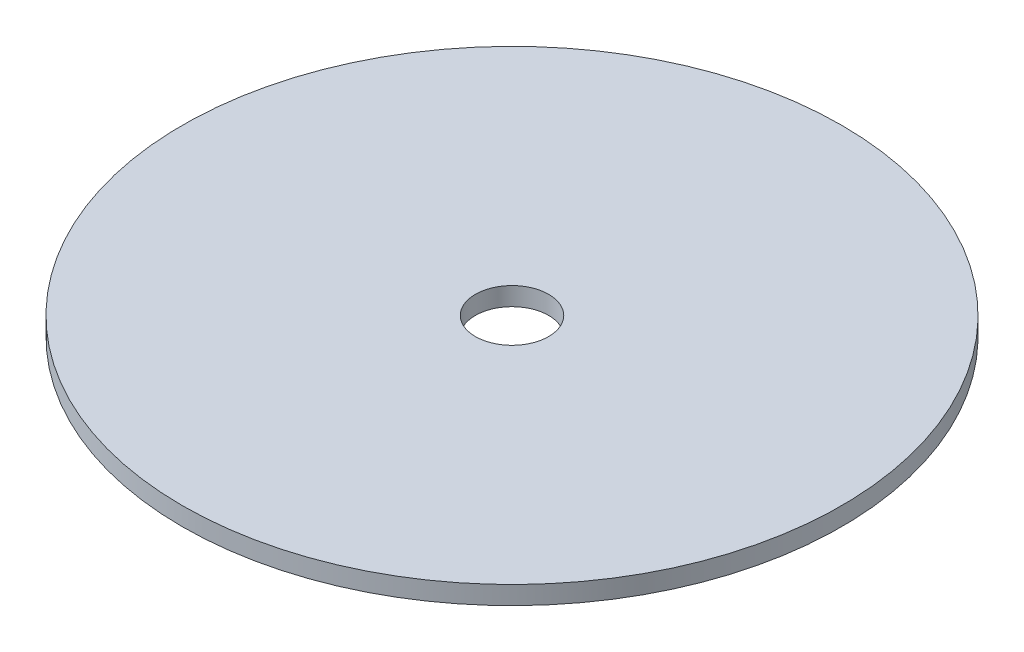
SolidWorks part; units mm, degrees
ref_plane "Front Plane" through (0, 0, 0) normal (0, 0, 1) x (1, 0, 0)
ref_plane "Top Plane" through (0, 0, 0) normal (0, 1, 0) x (1, 0, 0)
ref_plane "Right Plane" through (0, 0, 0) normal (1, 0, 0) x (0, 0, -1)
sketch "Sketch1" plane through (0, 0, 0) normal (0, 1, 0) x (1, 0, 0)
  circle A0 centre (0, 0) radius 36
  circle A1 centre (0, 0) radius 4
  dimension "D1" = 8
  dimension "D2" = 72
extrude "Boss-Extrude1" add sketch "Sketch1" along normal blind 2
